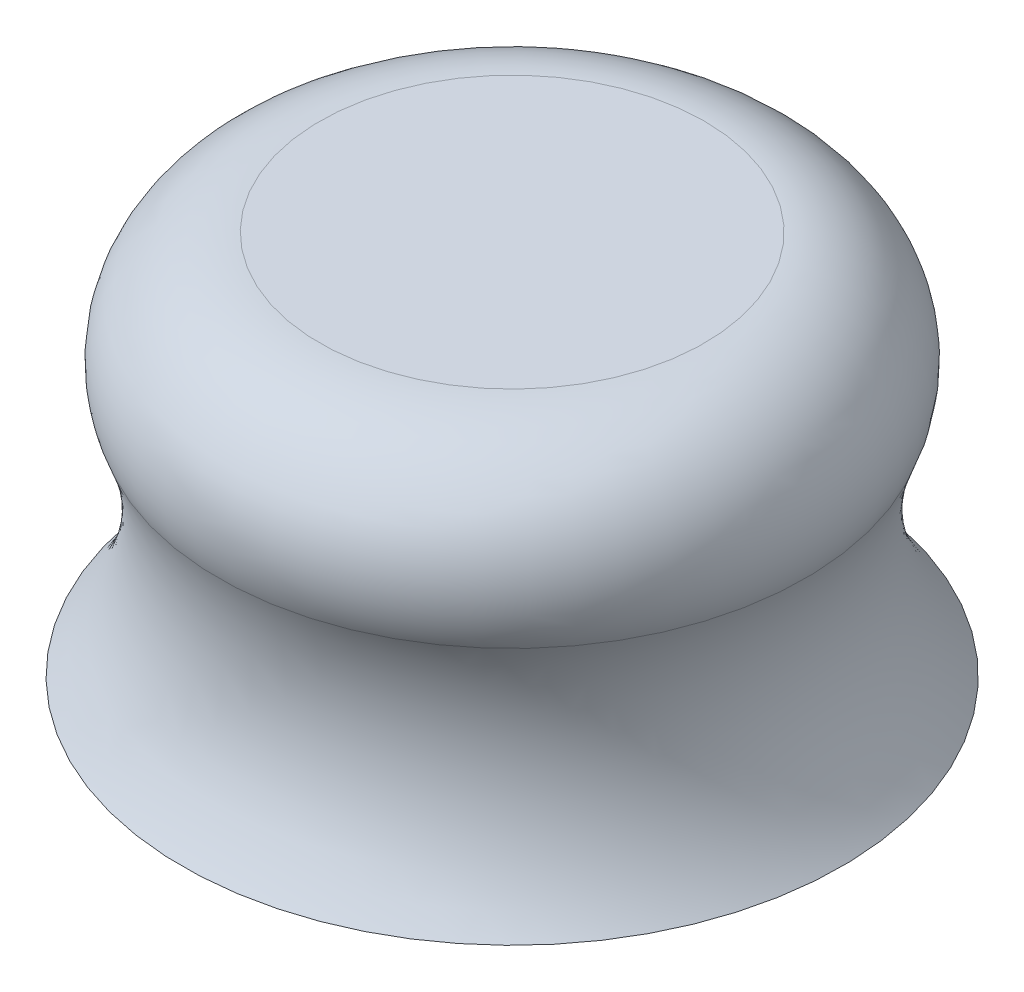
SolidWorks part; units mm, degrees
ref_plane "Front Plane" through (0, 0, 0) normal (0, 0, 1) x (1, 0, 0)
ref_plane "Top Plane" through (0, 0, 0) normal (0, 1, 0) x (1, 0, 0)
ref_plane "Right Plane" through (0, 0, 0) normal (1, 0, 0) x (0, 0, -1)
sketch "Sketch1" plane through (0, 0, 0) normal (1, 0, 0) x (0, 0, -1)
  line L0 (0, 0) -> (0, 35)
  line L1 (0, 35) -> (17.5, 35)
  line L2 (0, 0) -> (30, 0)
  arc A0 (17.5, 35) -> (26.6878, 21.0522) centre (17.5, 25) cw
  arc A1 (26.6878, 21.0522) -> (30, 0) centre (45.0633, 13.1566) ccw
  dimension "D2" = 10
  dimension "D3" = 20
  dimension "D1" = 35
  dimension "37/2" = 17.5
  dimension "D4" = 30
revolve "Revolve1" add sketch "Sketch1" angle 360 about L0
